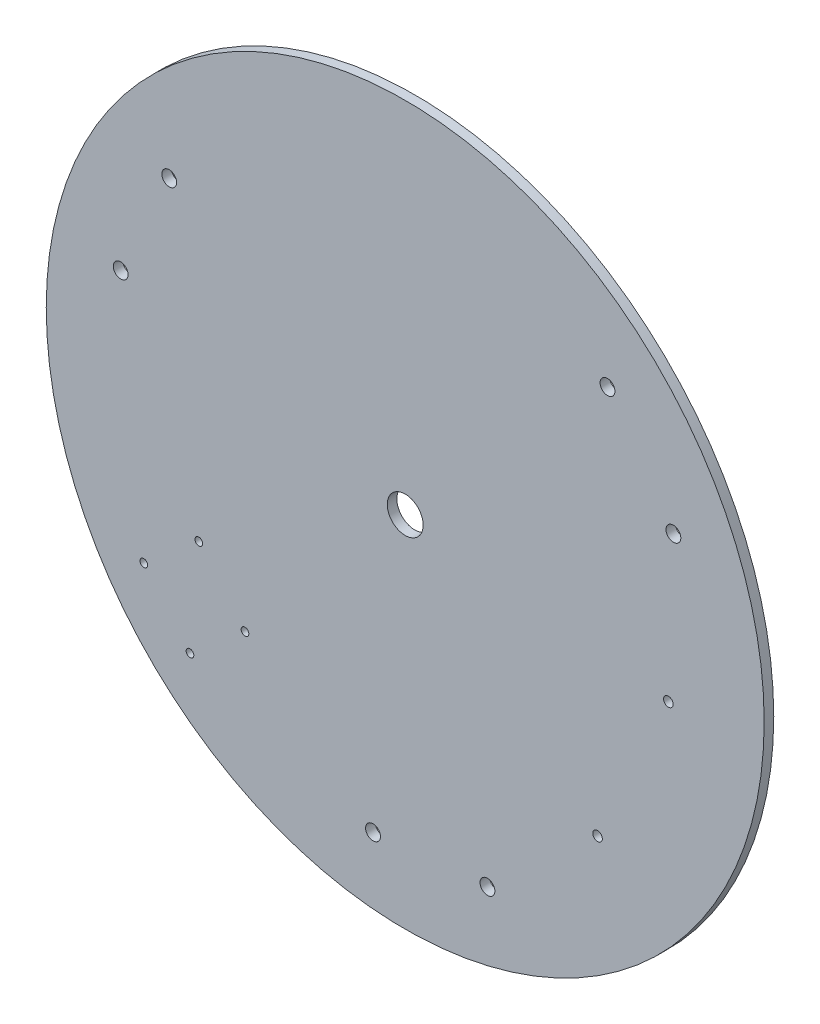
SolidWorks part; units mm, degrees
ref_plane "Front Plane" through (0, 0, 0) normal (0, 0, 1) x (1, 0, 0)
ref_plane "Top Plane" through (0, 0, 0) normal (0, 1, 0) x (1, 0, 0)
ref_plane "Right Plane" through (0, 0, 0) normal (1, 0, 0) x (0, 0, -1)
sketch "Sketch1" plane through (0, 0, 0) normal (0, 0, 1) x (1, 0, 0)
  circle A0 centre (0, 0) radius 150
  dimension "D1" = 300
extrude "Boss-Extrude1" add sketch "Sketch1" along normal blind 4
sketch "Sketch2" plane through (0, 0, 0) normal (0, 0, -1) x (-1, 0, 0)
  line L0 (0, 0) -> (0, 199.4542) construction
  line L1 (0, 0) -> (-183.0223, 128.1536) construction
  line L6 (-84.5324, 88.4888) -> (-112.0641, 49.1695) construction
  circle A0 centre (-84.5324, 88.4888) radius 3.1
  circle A1 centre (-112.0641, 49.1695) radius 3.1
  dimension "D6" = 6.2
  dimension "D1" = 55
  dimension "D2" = 24
  dimension "D3" = 120
extrude "Cut-Extrude1" cut sketch "Sketch2" against normal up to surface (4 mm away) up to face at (150, 0, 4)
pattern_circular "CirPattern1" count 3 over 360 about axis through (0, 0, 0) along (0, 0, 1) of "Cut-Extrude1"
sketch "Sketch3" plane through (0, 0, 0) normal (0, 0, -1) x (-1, 0, 0)
  line L0 (0, 0) -> (-135.9462, -63.3927) construction
  line L1 (-80.3707, -76.0957) -> (-109.954, -12.6541) construction
  line L2 (-84.5324, 88.4888) -> (-112.0641, 49.1695) construction
  line L4 (0, 0) -> (-98.2982, 68.8292) construction
  circle A0 centre (0, 0) radius 150 construction
  circle A1 centre (-109.954, -12.6541) radius 2
  circle A2 centre (-80.3707, -76.0957) radius 2
  dimension "D1" = 4
  dimension "D2" = 4
  dimension "D5" = 60
  dimension "D3" = 35
  dimension "D4" = 45
extrude "Cut-Extrude2" cut sketch "Sketch3" against normal up to surface (4 mm away) up to face at (37.4674, -117.4516, 4)
sketch "Sketch4" plane through (0, 0, 0) normal (0, 0, -1) x (-1, 0, 0)
  circle A0 centre (0, 0) radius 7.5
  dimension "D1" = 15
extrude "Cut-Extrude3" cut sketch "Sketch4" against normal up to surface (4 mm away) up to face at (111.954, -12.6541, 4)
sketch "Sketch6" plane through (0, 0, 0) normal (0, 0, -1) x (-1, 0, 0)
  line L0 (66.9626, -75.7694) -> (86.2463, -52.7881) construction
  line L2 (-34.3674, -117.4516) -> (13.45, -121.6351) construction
  line L4 (0, 0) -> (-10.4587, -119.5434) construction
  line L5 (0, 0) -> (146.4579, -122.8927) construction
  circle A4 centre (66.9626, -75.7694) radius 1.6
  circle A5 centre (89.944, -95.0531) radius 1.6
  circle A6 centre (109.2276, -72.0717) radius 1.6
  circle A7 centre (86.2463, -52.7881) radius 1.6
  dimension "D2" = 3.2
  dimension "D3" = 3.2
  dimension "D4" = 3.2
  dimension "D5" = 3.2
  dimension "D6" = 15
  dimension "D7" = 15
  dimension "D8" = 30
  dimension "D9" = 100
  dimension "D10" = 55
extrude "Cut-Extrude5" cut sketch "Sketch6" against normal up to surface (4 mm away) up to face at (7.5, 0, 4)
